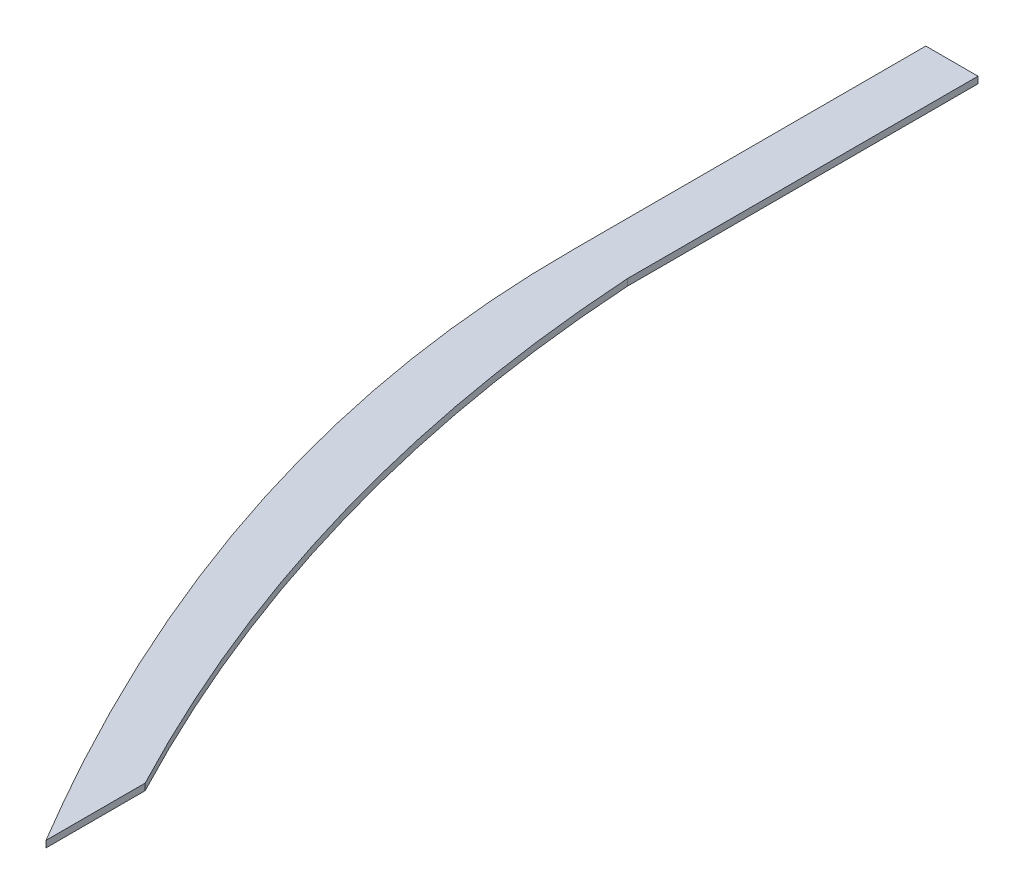
SolidWorks part; units mm, degrees
ref_plane "Front Plane" through (0, 0, 0) normal (0, 0, 1) x (1, 0, 0)
ref_plane "Top Plane" through (0, 0, 0) normal (0, 1, 0) x (1, 0, 0)
ref_plane "Right Plane" through (0, 0, 0) normal (1, 0, 0) x (0, 0, -1)
sketch "Sketch1" plane through (0, 0, 0) normal (0, 1, 0) x (1, 0, 0)
  line L0 (-82.882, 336.4126) -> (-82.882, 124.4126)
  line L1 (-82.882, 336.4126) -> (-51.3126, 336.4126)
  line L2 (-51.3126, 336.4126) -> (-51.3126, 124.4126)
  line L3 (67.118, -345.8005) -> (67.118, -285.8272)
  spline S0 degree 2 poles (-82.882, 124.4126) (-84.1577, -91.9903) (67.118, -345.8005) knots 0 0 0 1 1 1
  spline S1 degree 2 poles (-51.3126, 124.4126) (-38.2842, -84.7184) (67.118, -285.8272) knots 0 0 0 1 1 1
extrude "Boss-Extrude1" add sketch "Sketch1" along normal blind 4
ref_plane "Plane1" through (0, 2, 0) normal (0, 1, 0) x (1, 0, 0)
